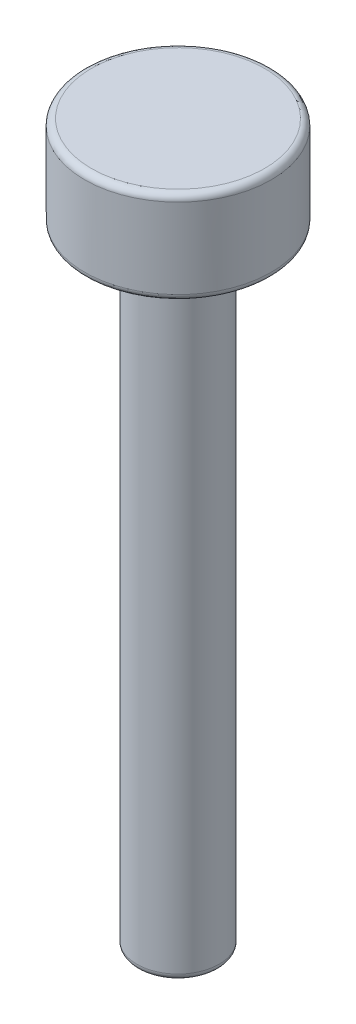
SolidWorks part; units mm, degrees
ref_plane "Front Plane" through (0, 0, 0) normal (0, 0, 1) x (1, 0, 0)
ref_plane "Top Plane" through (0, 0, 0) normal (0, 1, 0) x (1, 0, 0)
ref_plane "Right Plane" through (0, 0, 0) normal (1, 0, 0) x (0, 0, -1)
sketch "Sketch1" plane through (0, 0, 0) normal (0, 0, 1) x (1, 0, 0)
  line L0 (0, 0) -> (4.7625, 0)
  line L1 (4.7625, 0) -> (4.7625, 72.39)
  line L2 (0, 0) -> (0, 83.185)
  line L3 (4.7625, 72.39) -> (10.795, 72.39)
  line L4 (10.795, 72.39) -> (10.795, 83.185)
  line L5 (10.795, 83.185) -> (0, 83.185)
  point P8 (0, 87.372)
  dimension "D1" = 72.39
  dimension "D2" = 4.7625
  dimension "D3" = 6.0325
  dimension "D4" = 10.795
revolve "Revolve1" add sketch "Sketch1" angle 360 about L2
fillet "Fillet1" radius 0.762 3 edges at (0, 72.39, -10.795) (0, 83.185, -10.795) (0, 0, -4.7625)
